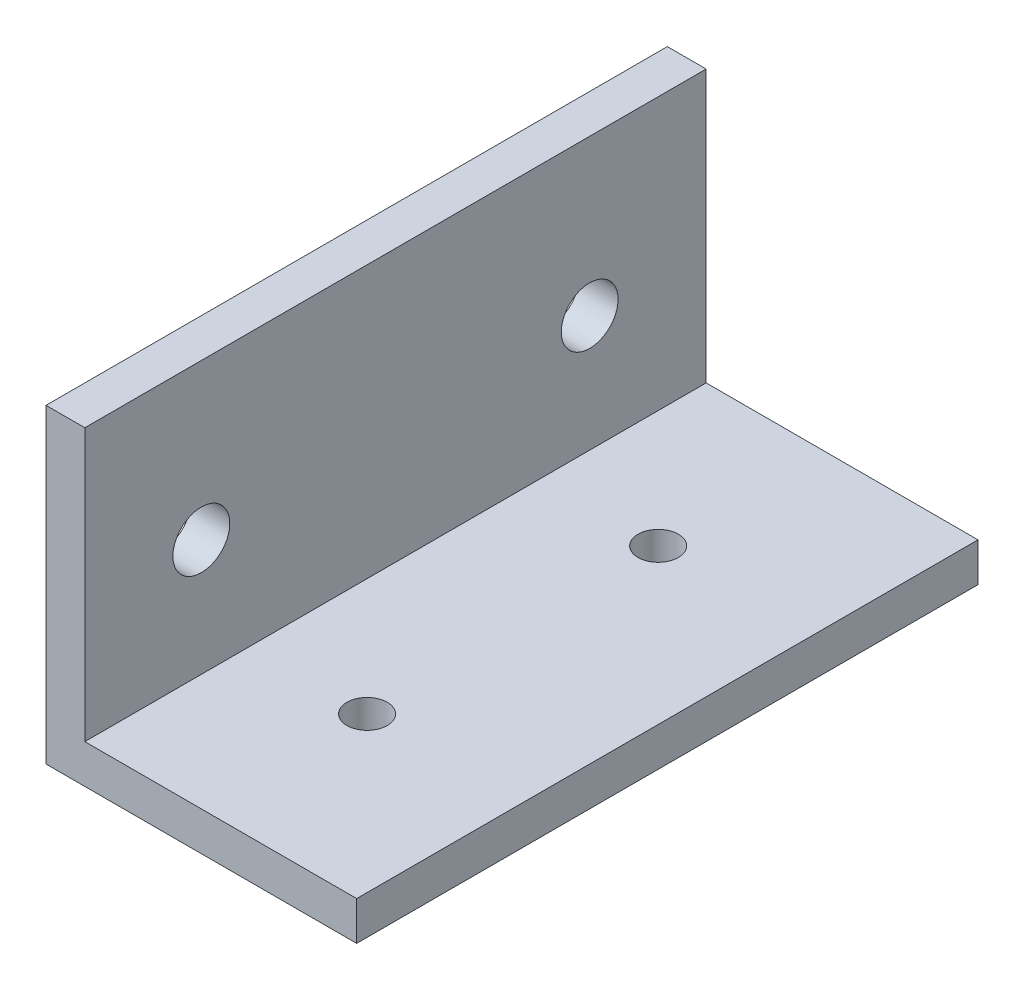
SolidWorks part; units mm, degrees
material "AISI 316 Annealed Stainless Steel Bar (SS)"
ref_plane "Front Plane" through (0, 0, 0) normal (0, 0, 1) x (1, 0, 0)
ref_plane "Top Plane" through (0, 0, 0) normal (0, 1, 0) x (1, 0, 0)
ref_plane "Right Plane" through (0, 0, 0) normal (1, 0, 0) x (0, 0, -1)
sketch "Sketch1" plane through (0, 0, 0) normal (0, 0, 1) x (1, 0, 0)
  line L0 (0, 25.4) -> (0, 0)
  line L1 (0, -64.5222) -> (0, 64.5222) construction
  line L2 (0, 0) -> (25.4, 0)
  line L3 (67.2731, 0) -> (-67.2731, 0) construction
  line L4 (3.175, 25.4) -> (3.175, 3.175)
  line L5 (3.175, 3.175) -> (25.4, 3.175)
  line L6 (0, 25.4) -> (3.175, 25.4)
  line L7 (25.4, 3.175) -> (25.4, 0)
  dimension "D1" = 25.4
  dimension "D2" = 3.175
extrude "Boss-Extrude1" add sketch "Sketch1" along normal blind 50.8
sketch "Sketch2" plane through (0, 3.175, 0) normal (0, 1, 0) x (1, 0, 0)
  circle A0 centre (12.75, -13.5) radius 1.65
  circle A1 centre (12.75, -37.3) radius 1.65
extrude "Cut-Extrude1" cut sketch "Sketch2" against normal through all
sketch "Sketch3" plane through (0, 0, 0) normal (-1, 0, 0) x (0, 0, 1)
  line L0 (50.8, 12.7) -> (0, 12.7) construction
  line L1 (50.8, 25.4) -> (50.8, 0) construction
  line L2 (0, -64.6286) -> (0, 64.6286) construction
  circle A0 centre (9.525, 12.7) radius 2.3241
  circle A1 centre (41.275, 12.7) radius 2.3241
  dimension "D1" = 4.6482
  dimension "D2" = 31.75
  dimension "D3" = 9.525
extrude "Cut-Extrude2" cut sketch "Sketch3" against normal through all
equation "\"D3@Sketch3\"=(2-\"D2@Sketch3\")/2"
